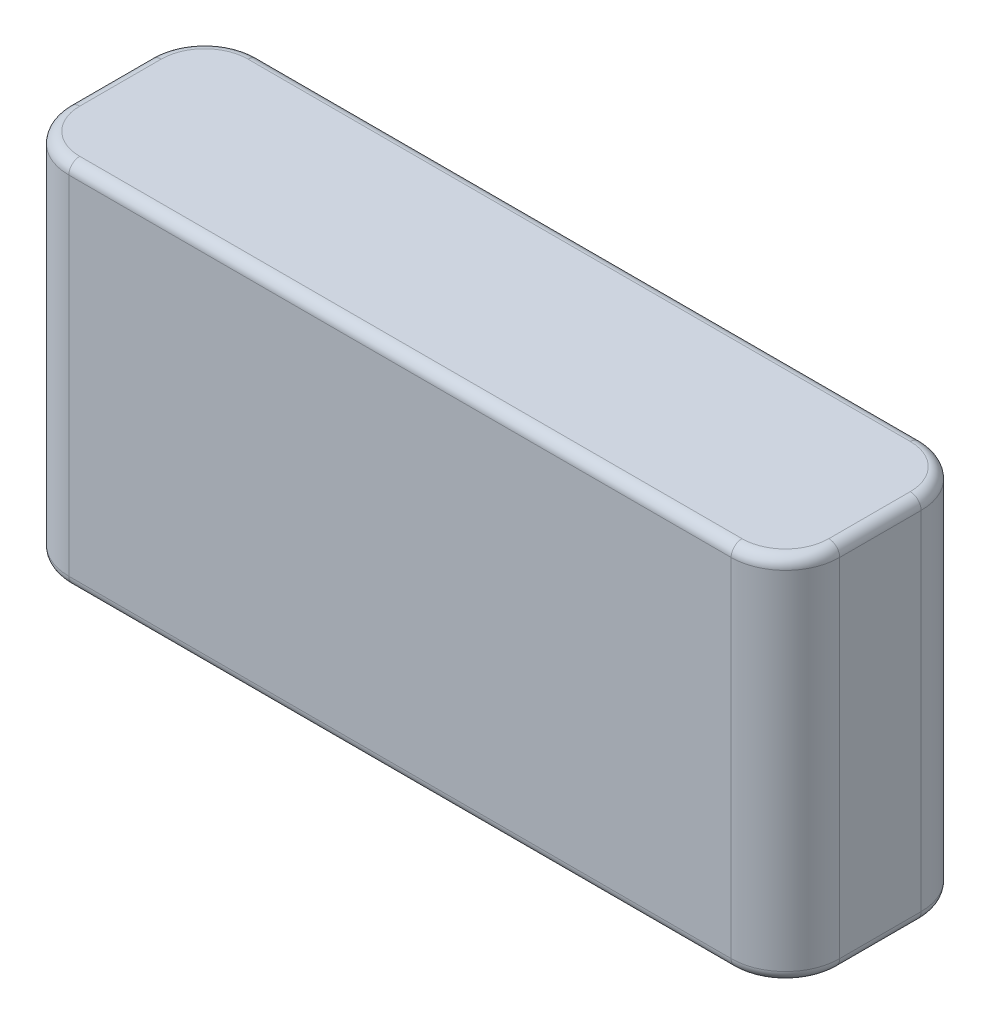
SolidWorks part; units mm, degrees
ref_plane "Front Plane" through (0, 0, 0) normal (0, 0, 1) x (1, 0, 0)
ref_plane "Top Plane" through (0, 0, 0) normal (0, 1, 0) x (1, 0, 0)
ref_plane "Right Plane" through (0, 0, 0) normal (1, 0, 0) x (0, 0, -1)
sketch "Sketch1" plane through (0, 0, 0) normal (0, 0, 1) x (1, 0, 0)
  line L1 (-35.5, -17) -> (35.5, -17)
  line L2 (-35.5, -17) -> (-35.5, 17)
  line L3 (-35.5, 17) -> (35.5, 17)
  line L4 (35.5, -17) -> (35.5, 17)
  line L5 (-35.5, -17) -> (35.5, 17) construction
  line L6 (-35.5, 17) -> (35.5, -17) construction
  point P0 (0, 0)
  dimension "D1" = 71
  dimension "D2" = 34
extrude "Boss-Extrude1" add sketch "Sketch1" along normal mid plane 17.5
fillet "Fillet1" radius 5 4 edges at (35.5, 0, -8.75) (35.5, 0, 8.75) (-35.5, 0, 8.75) (-35.5, 0, -8.75)
fillet "Fillet2" radius 1 16 edges at (-34.0355, -17, -7.2855) (-35.5, -17, 0) (-34.0355, -17, 7.2855) (0, -17, 8.75) (34.0355, -17, 7.2855) (35.5, -17, 0) (34.0355, -17, -7.2855) (0, -17, -8.75) (34.0355, 17, 7.2855) (0, 17, 8.75) (-34.0355, 17, 7.2855) (-35.5, 17, 0) (-34.0355, 17, -7.2855) (0, 17, -8.75) (34.0355, 17, -7.2855) (35.5, 17, 0)
